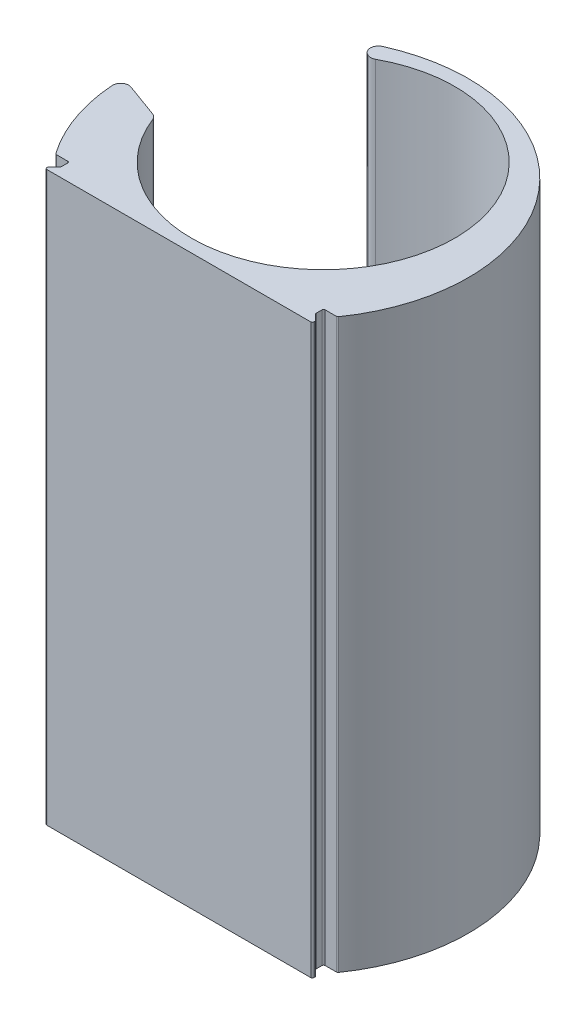
SolidWorks part; units mm, degrees
ref_plane "Front Plane" through (0, 0, 0) normal (0, 0, 1) x (1, 0, 0)
ref_plane "Top Plane" through (0, 0, 0) normal (0, 1, 0) x (1, 0, 0)
ref_plane "Right Plane" through (0, 0, 0) normal (1, 0, 0) x (0, 0, -1)
sketch "Sketch1" plane through (0, 0, 0) normal (0, 1, 0) x (1, 0, 0)
  line L0 (-19.1484, -30.0361) -> (-16.2484, -30.0361) construction
  line L1 (-16.2484, -30.0361) -> (-18.4484, -27.8361) construction
  line L2 (-18.4484, -27.8361) -> (-19.9484, -27.8361) construction
  line L3 (-19.9484, -27.8361) -> (-19.9484, -28.6361) construction
  line L4 (-19.9484, -28.6361) -> (-19.1484, -29.4361) construction
  line L5 (-19.1484, -29.4361) -> (-19.1484, -30.0361) construction
  line L6 (-55.6484, -30.0361) -> (-52.7484, -30.0361) construction
  line L7 (-52.7484, -30.0361) -> (-52.7484, -29.4361) construction
  line L8 (-52.7484, -29.4361) -> (-51.9484, -28.6361) construction
  line L9 (-51.9484, -28.6361) -> (-51.9484, -27.8361) construction
  line L10 (-51.9484, -27.8361) -> (-53.4484, -27.8361) construction
  line L11 (-53.4484, -27.8361) -> (-55.6484, -30.0361) construction
  line L12 (-19.2984, -30.1861) -> (-15.8863, -30.1861) construction
  line L13 (-15.8863, -30.1861) -> (-18.3863, -27.6861) construction
  line L14 (-18.3863, -27.6861) -> (-20.0984, -27.6861)
  line L15 (-20.0984, -27.6861) -> (-20.0984, -28.6982)
  line L16 (-20.0984, -28.6982) -> (-19.2984, -29.4982)
  line L17 (-19.2984, -29.4982) -> (-19.2984, -29.8861)
  line L18 (-56.0106, -30.1861) -> (-52.5984, -30.1861) construction
  line L19 (-52.5984, -29.8861) -> (-52.5984, -29.4982)
  line L20 (-52.5984, -29.4982) -> (-51.7984, -28.6982)
  line L21 (-51.7984, -28.6982) -> (-51.7984, -27.6861)
  line L22 (-51.7984, -27.6861) -> (-53.5106, -27.6861)
  line L23 (-53.5106, -27.6861) -> (-56.0106, -30.1861) construction
  line L24 (-52.5984, -29.8861) -> (-19.2984, -29.8861)
  line L25 (-19.2984, -29.4982) -> (-19.2984, -30.1861) construction
  line L26 (-52.5984, -30.1861) -> (-52.5984, -29.4982) construction
  circle A1 centre (-35.9484, -11.8861) radius 16.4
  arc A2 (-53.5106, -27.6861) -> (-18.3863, -27.6861) centre (-35.9484, -15.2836) cw
  point P28 (-35.9484, -13.3861)
  point P30 (-29.1385, -13.3861)
  dimension "D4" = 32.8
  dimension "D5" = 21.5
  dimension "D2" = 0.15
  dimension "D3" = 18
  dimension "D1" = 0.15
extrude "Boss-Extrude1" add sketch "Sketch1" along normal blind 70
sketch "Sketch2" plane through (0, 0, 0) normal (0, -1, 0) x (1, 0, 0)
  line L9 (-18.3863, 27.6861) -> (-20.0984, 27.6861)
  line L10 (-20.0984, 27.6861) -> (-20.0984, 28.6982)
  line L11 (-20.0984, 28.6982) -> (-19.2984, 29.4982)
  line L12 (-19.2984, 29.4982) -> (-19.2984, 29.8861)
  line L13 (-19.2984, 29.8861) -> (-52.5984, 29.8861)
  line L14 (-52.5984, 29.8861) -> (-52.5984, 29.4982)
  line L15 (-52.5984, 29.4982) -> (-51.7984, 28.6982)
  line L16 (-51.7984, 28.6982) -> (-51.7984, 27.6861)
  line L17 (-51.7984, 27.6861) -> (-53.5106, 27.6861)
  line L18 (-18.3863, 27.6861) -> (-20.0984, 27.6861)
  line L19 (-20.0984, 27.6861) -> (-20.0984, 28.6982)
  line L20 (-20.0984, 28.6982) -> (-19.2984, 29.4982)
  line L21 (-19.2984, 29.4982) -> (-19.2984, 29.8861)
  line L22 (-19.2984, 29.8861) -> (-52.5984, 29.8861)
  line L23 (-52.5984, 29.8861) -> (-52.5984, 29.4982)
  line L24 (-52.5984, 29.4982) -> (-51.7984, 28.6982)
  line L25 (-51.7984, 28.6982) -> (-51.7984, 27.6861)
  line L26 (-51.7984, 27.6861) -> (-53.5106, 27.6861)
  arc A1 (-53.5106, 27.6861) -> (-18.3863, 27.6861) centre (-35.9484, 15.2836) ccw
  arc A2 (-53.5106, 27.6861) -> (-18.3863, 27.6861) centre (-35.9484, 15.2836) ccw
  dimension "D1" = 0
extrude "Boss-Extrude2" add sketch "Sketch2" along normal blind 0.8
sketch "Sketch3" plane through (0, 70, 0) normal (0, 1, 0) x (1, 0, 0)
  line L0 (-49.616, -18.0854) -> (-42.4335, 1.6482)
  line L1 (-49.616, -18.0854) -> (-64.5965, -12.6329)
  line L2 (-42.4335, 1.6482) -> (-57.4141, 7.1006)
  line L3 (-64.5965, -12.6329) -> (-57.4141, 7.1006)
  line L4 (-35.6319, -29.8861) -> (-67.0908, -29.8861) construction
  line L5 (-52.5984, -29.8861) -> (-19.2984, -29.8861) construction
  line L6 (-35.9484, -11.8861) -> (-46.0248, -8.2186) construction
  point P6 (-44.9304, -10.0054)
  dimension "D1" = 20
  dimension "D2" = 21
extrude "Cut-Extrude1" cut sketch "Sketch3" against normal blind 64
fillet "Fillet1" radius 1 4 edges at (-57.4484, 38, 15.2346) (-46.8416, 38, -3.2526) (-51.3779, 38, 17.4441) (-44.1955, 38, -2.2895)
fillet "Fillet2" radius 0.2 10 edges at (-18.3863, 34.6, 27.6861) (-20.0984, 34.6, 27.6861) (-20.0984, 34.6, 28.6982) (-19.2984, 34.6, 29.4982) (-19.2984, 34.6, 29.8861) (-52.5984, 34.6, 29.8861) (-52.5984, 34.6, 29.4982) (-51.7984, 34.6, 28.6982) (-51.7984, 34.6, 27.6861) (-53.5106, 34.6, 27.6861)
sketch "Sketch4" plane through (0, 0, 0) normal (1, 0, 0) x (0, 0, -1)
  line L0 (5.2002, -1.5456) -> (6.9524, 1.5449)
  line L1 (6.9524, 1.5449) -> (6.9524, -1.5456)
  line L2 (6.9524, -1.5456) -> (5.2002, -1.5456)
  point P4 (6.9524, 1.5449)
  point P5 (5.2024, -1.5607)
extrude "Cut-Extrude2" [suppressed] cut sketch "Sketch4" against normal through all both and the other way through all
